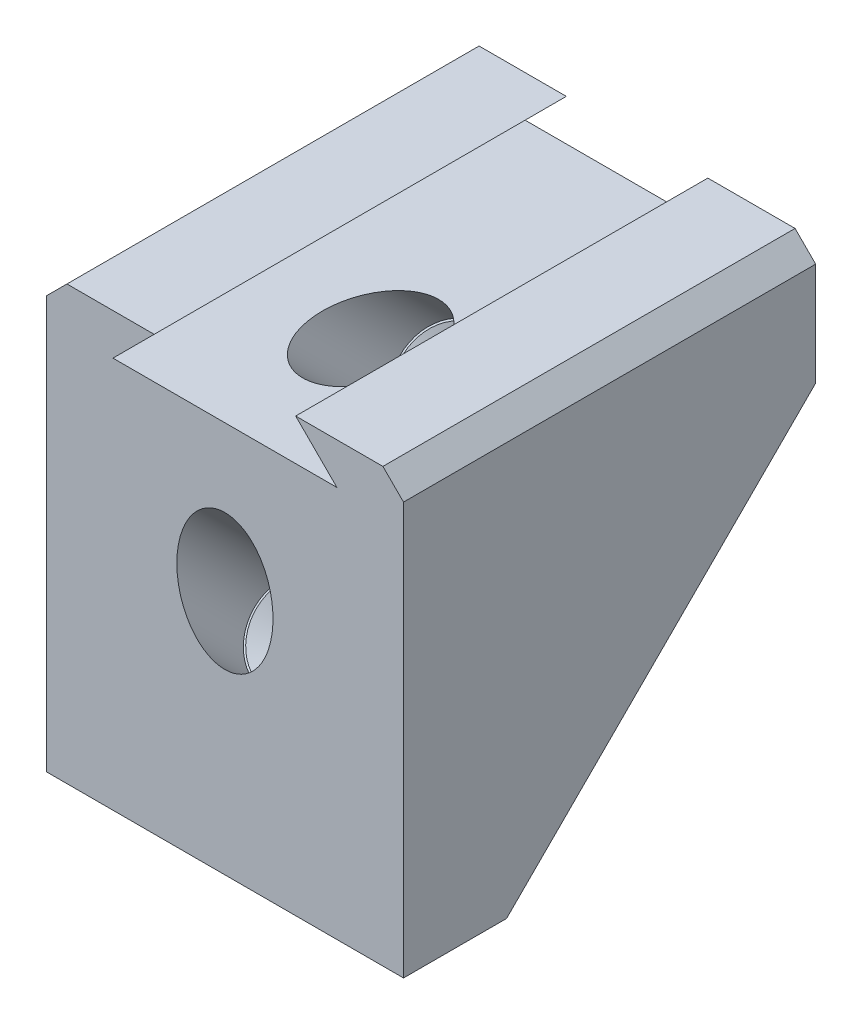
SolidWorks part; units mm, degrees
ref_plane "Front Plane" through (0, 0, 0) normal (0, 0, 1) x (1, 0, 0)
ref_plane "Top Plane" through (0, 0, 0) normal (0, 1, 0) x (1, 0, 0)
ref_plane "Right Plane" through (0, 0, 0) normal (1, 0, 0) x (0, 0, -1)
sketch "Sketch2" plane through (0, 0, 0) normal (0, 0, 1) x (1, 0, 0)
  line L0 (-13, 0) -> (13, 0)
  line L1 (13, 0) -> (13, 7.5)
  line L2 (13, 7.5) -> (11.5, 9)
  line L3 (11.5, 9) -> (5.15, 9)
  line L4 (5.15, 9) -> (8.15, 6)
  line L5 (8.15, 6) -> (-8.15, 6)
  line L6 (-8.15, 6) -> (-5.15, 9)
  line L7 (-5.15, 9) -> (-11.5, 9)
  line L8 (-11.5, 9) -> (-13, 7.5)
  line L9 (-13, 7.5) -> (-13, 0)
  point P0 (0, 0)
  point P12 (0, 6)
  dimension "D1" = 16.3
  dimension "D2" = 45
  dimension "D3" = 3
  dimension "D4" = 45
  dimension "D5" = 26
  dimension "D6" = 1.5
  dimension "D7" = 1.5
  dimension "D8" = 6
extrude "Boss-Extrude1" add sketch "Sketch2" along normal blind 30
sketch "Sketch3" plane through (13, 0, 0) normal (1, 0, 0) x (0, 0, -1)
  line L0 (-30, 0) -> (-30, -22.5)
  line L1 (-22.5, -22.5) -> (0, 0)
  line L2 (-30, 0) -> (0, 0) construction
  line L3 (-30, 0) -> (0, 0)
  line L4 (-22.5, -22.5) -> (-30, -22.5)
  line L5 (0, 0) -> (0, 7.5) construction
  dimension "D1" = 45
extrude "Boss-Extrude2" add sketch "Sketch3" against normal up to surface (26 mm away) up to face at (-13, 3.75, 15)
ref_plane "Plane1" through (0, 7.0711, 7.0711) normal (0, 0.7071, 0.7071) x (1, 0, 0)
sketch "Sketch6" plane through (0, 7.0711, 7.0711) normal (0, 0.7071, 0.7071) x (1, 0, 0)
  line L0 (0, -9.4706) -> (0, -16.9706) construction
  line L1 (8.15, -16.9706) -> (-8.15, -16.9706) construction
  line L2 (0, -16.9706) -> (0, -24.4706) construction
  point P0 (0, -9.4706)
  point P1 (0, -24.4706)
  dimension "D1" = 15
sketch "Sketch8" plane through (0, 7.0711, 7.0711) normal (0, 0.7071, 0.7071) x (1, 0, 0)
  circle A0 centre (0, -9.4706) radius 3.5
  circle A1 centre (0, -24.4706) radius 3.5
  dimension "D1" = 7
extrude "Cut-Extrude1" cut sketch "Sketch8" along normal up to next
sketch "Sketch12" plane through (0, 7.0711, 7.0711) normal (0, 0.7071, 0.7071) x (1, 0, 0)
  point P0 (0, -9.4706)
  point P3 (0, -24.4706)
hole_wizard "CSK for M3 Hex Socket Countersunk Cap Screw3" positions "Sketch12" profile "Sketch10" countersink size "M3" standard "ISO" end condition up to next
sketch "Sketch10" plane through (0, 0.3744, 13.7678) normal (1, 0, 0) x (0, -0.7071, 0.7071)
  line L0 (0, 0) -> (0, 10)
  line L1 (0, 10) -> (1.7, 10)
  line L2 (1.7, 10) -> (1.7, 1.66)
  line L3 (1.7, 1.66) -> (3.36, 0)
  line L5 (3.36, 0) -> (0, 0)
  line L6 (-1.7, 1.66) -> (-3.36, 0) construction
  line L11 (0, -6.35) -> (0, 107.95) construction
  dimension "Thru Hole Dia." = 3.4
  dimension "Thru Hole Depth" = 10
  dimension "Near C'Sink Dia." = 6.72
  dimension "Near C'Sink Angle" = 90
